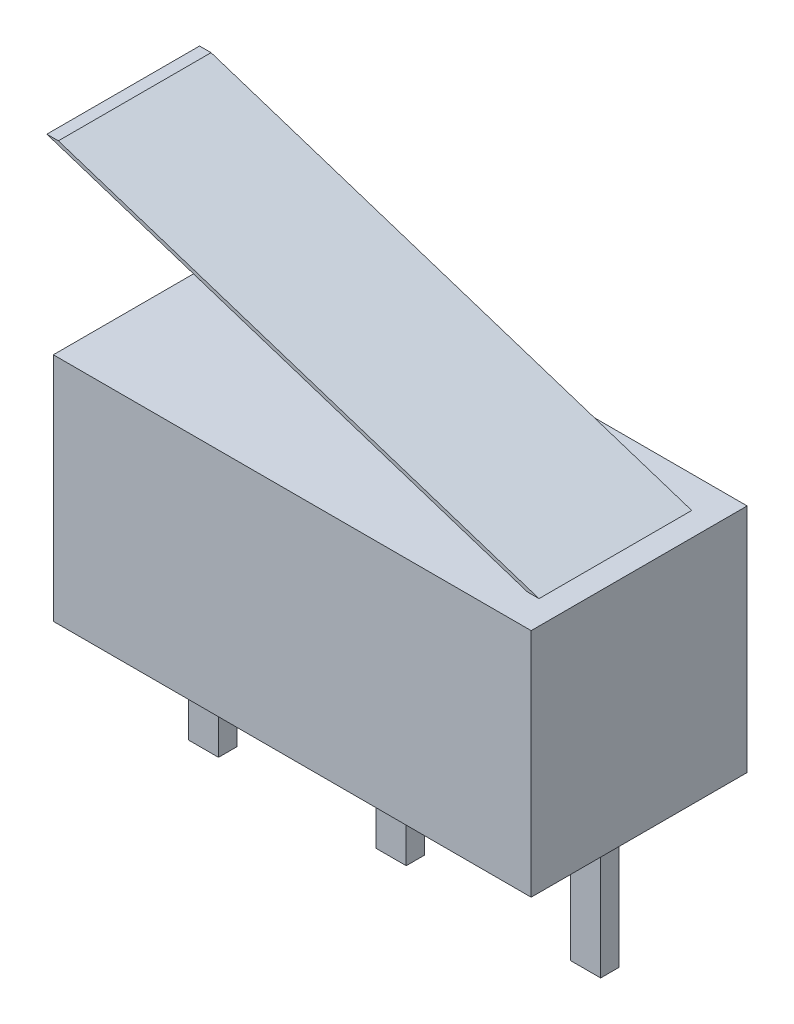
SolidWorks part; units mm, degrees
ref_plane "Front Plane" through (0, 0, 0) normal (0, 0, 1) x (1, 0, 0)
ref_plane "Top Plane" through (0, 0, 0) normal (0, 1, 0) x (1, 0, 0)
ref_plane "Right Plane" through (0, 0, 0) normal (1, 0, 0) x (0, 0, -1)
sketch "Sketch1" plane through (0, 0, 0) normal (0, 1, 0) x (1, 0, 0)
  line L1 (-6.415, -2.9) -> (6.415, -2.9)
  line L2 (-6.415, -2.9) -> (-6.415, 2.9)
  line L3 (-6.415, 2.9) -> (6.415, 2.9)
  line L4 (6.415, -2.9) -> (6.415, 2.9)
  line L5 (-6.415, -2.9) -> (6.415, 2.9) construction
  line L6 (-6.415, 2.9) -> (6.415, -2.9) construction
  point P0 (0, 0)
  dimension "D1" = 5.8
  dimension "D2" = 12.83
extrude "Boss-Extrude1" add sketch "Sketch1" along normal blind 6.2
sketch "Sketch2" plane through (0, 6.2, 0) normal (0, 1, 0) x (1, 0, 0)
  line L1 (5.4662, 2.05) -> (5.7762, 2.05)
  line L2 (5.4662, 2.05) -> (5.4662, -2.05)
  line L3 (5.4662, -2.05) -> (5.7762, -2.05)
  line L4 (5.7762, 2.05) -> (5.7762, -2.05)
  line L5 (5.4662, 2.05) -> (5.7762, -2.05) construction
  line L6 (5.4662, -2.05) -> (5.7762, 2.05) construction
  point P0 (5.6212, 0)
  dimension "D1" = 4.1
  dimension "D2" = 0.31
sketch "Sketch3" plane through (0, 0, 2.9) normal (0, 0, 1) x (1, 0, 0)
  line L0 (5.6212, 6.2) -> (-7.2849, 10.3926)
  line L1 (-6.415, 6.2) -> (-6.415, 10.11) construction
  dimension "D1" = 3.91
  dimension "D2" = 13.57
sweep "Sweep1" add profiles "Sketch2" path "Sketch3"
sketch "Sketch4" plane through (0, 0, 0) normal (0, -1, 0) x (1, 0, 0)
  line L0 (-6.415, -2.9) -> (-6.415, 2.9) construction
  line L1 (-5.445, -0.245) -> (-4.635, -0.245)
  line L2 (-5.445, -0.245) -> (-5.445, 0.245)
  line L3 (-5.445, 0.245) -> (-4.635, 0.245)
  line L4 (-4.635, -0.245) -> (-4.635, 0.245)
  line L5 (-5.445, -0.245) -> (-4.635, 0.245) construction
  line L6 (-5.445, 0.245) -> (-4.635, -0.245) construction
  line L7 (-0.405, -0.245) -> (0.405, -0.245)
  line L8 (-0.405, -0.245) -> (-0.405, 0.245)
  line L9 (-0.405, 0.245) -> (0.405, 0.245)
  line L10 (0.405, -0.245) -> (0.405, 0.245)
  line L11 (-0.405, -0.245) -> (0.405, 0.245) construction
  line L12 (-0.405, 0.245) -> (0.405, -0.245) construction
  line L13 (4.8159, -0.245) -> (5.6259, -0.245)
  line L14 (4.8159, -0.245) -> (4.8159, 0.245)
  line L15 (4.8159, 0.245) -> (5.6259, 0.245)
  line L16 (5.6259, -0.245) -> (5.6259, 0.245)
  line L17 (4.8159, -0.245) -> (5.6259, 0.245) construction
  line L18 (4.8159, 0.245) -> (5.6259, -0.245) construction
  point P0 (-5.04, 0)
  point P5 (0, 0)
  point P11 (5.2209, 0)
  dimension "D1" = 0.97
  dimension "D2" = 0.81
  dimension "D3" = 0.49
extrude "Boss-Extrude2" add sketch "Sketch4" along normal blind 3.6
